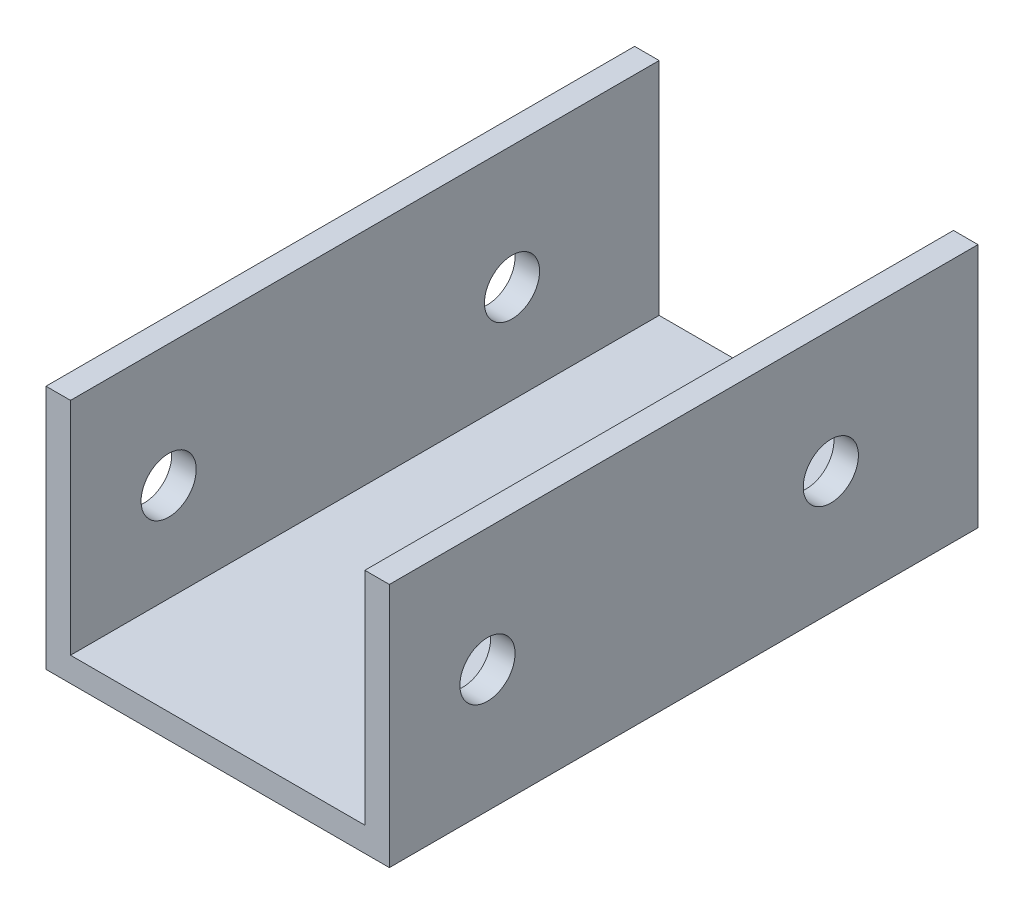
SolidWorks part; units mm, degrees
ref_plane "Front Plane" through (0, 0, 0) normal (0, 0, 1) x (1, 0, 0)
ref_plane "Top Plane" through (0, 0, 0) normal (0, 1, 0) x (1, 0, 0)
ref_plane "Right Plane" through (0, 0, 0) normal (1, 0, 0) x (0, 0, -1)
sketch "Sketch2" plane through (0, 0, 0) normal (0, 0, 1) x (1, 0, 0)
  line L1 (-22.225, 15.875) -> (22.225, 15.875)
  line L2 (-22.225, 15.875) -> (-22.225, -15.875)
  line L3 (-22.225, -15.875) -> (22.225, -15.875)
  line L4 (22.225, 15.875) -> (22.225, -15.875)
  line L5 (-22.225, 15.875) -> (22.225, -15.875) construction
  line L6 (-22.225, -15.875) -> (22.225, 15.875) construction
  line L7 (-19.05, 15.875) -> (19.05, 15.875)
  line L8 (-19.05, 15.875) -> (-19.05, -12.7)
  line L9 (-19.05, -12.7) -> (19.05, -12.7)
  line L10 (19.05, 15.875) -> (19.05, -12.7)
  point P0 (0, 0)
  point P10 (0, -12.7)
  dimension "D1" = 44.45
  dimension "D2" = 31.75
  dimension "D3" = 3.175
  dimension "D4" = 3.175
extrude "Boss-Extrude1" add sketch "Sketch2" along normal blind 76.2 contours L1 L10 L9 L8 L2 L3 L4
hole_wizard "1/4 Clearance Hole1" positions "Sketch3" profile "Sketch4" hole size "1/4" standard "ANSI Inch" end condition through all
sketch "Sketch3" plane through (22.225, 0, 0) normal (1, 0, 0) x (0, 0, -1)
  line L0 (-76.2, -15.875) -> (-76.2, 0) construction
  line L1 (-76.2, 15.875) -> (-76.2, -15.875) construction
  line L2 (-76.2, 0) -> (-63.5, 0) construction
  line L3 (0, 15.875) -> (0, -15.875) construction
  point P7 (-63.5, 0)
  point P12 (-19.05, 0)
  dimension "D1" = 15.875
  dimension "D2" = 12.7
  dimension "D3" = 19.05
sketch "Sketch4" plane through (22.225, 0, 19.05) normal (0, 1, 0) x (0, 0, -1)
  line L0 (0, 0) -> (0, 44.45)
  line L1 (0, 44.45) -> (3.5712, 44.45)
  line L2 (3.5712, 44.45) -> (3.5712, 0)
  line L5 (3.5712, 0) -> (0, 0)
  line L11 (0, -6.35) -> (0, 107.95) construction
  dimension "Thru Hole Dia." = 7.1425
  dimension "Thru Hole Depth" = 44.45
